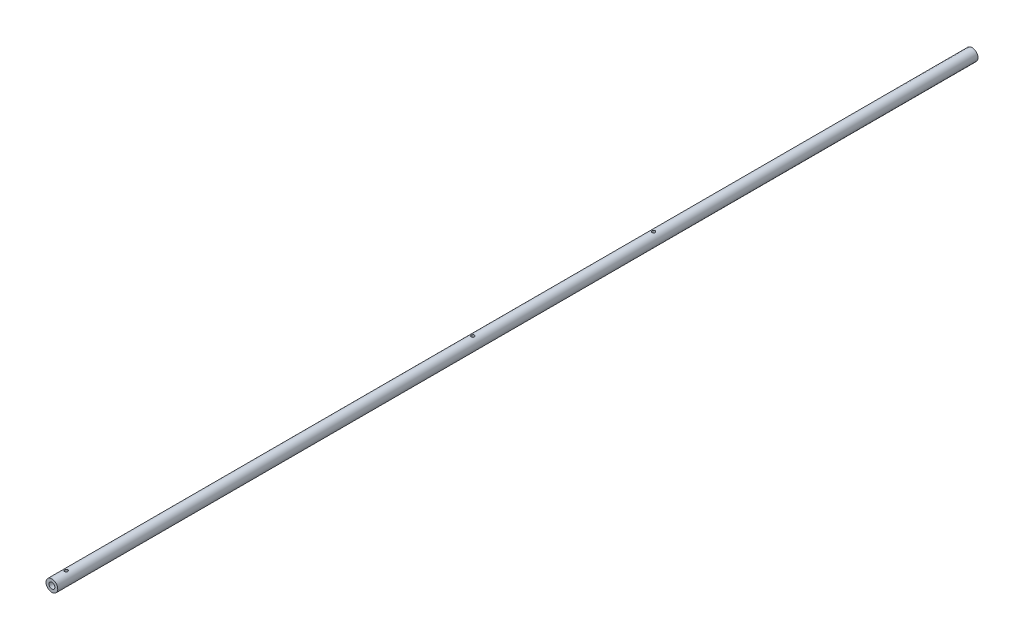
SolidWorks part; units mm, degrees
ref_plane "Front Plane" through (0, 0, 0) normal (0, 0, 1) x (1, 0, 0)
ref_plane "Top Plane" through (0, 0, 0) normal (0, 1, 0) x (1, 0, 0)
ref_plane "Right Plane" through (0, 0, 0) normal (1, 0, 0) x (0, 0, -1)
sketch "Sketch1" plane through (0, 0, 0) normal (0, 0, 1) x (1, 0, 0)
  circle A0 centre (0, 0) radius 3.9306
  circle A1 centre (0, 0) radius 7.8613
  dimension "D1" = 15.7226
  dimension "D2" = 7.8613
extrude "Rod" add sketch "Sketch1" along normal blind 1228.725 contours A0
sketch "Sketch3" plane through (0, 0, 0) normal (0, 1, 0) x (1, 0, 0)
  line L0 (0, -425.45) -> (0, -962.025) construction
  line L1 (-7.8613, -1228.725) -> (7.8613, -1228.725) construction
  circle A0 centre (0, -425.45) radius 2.1082
  circle A4 centre (0, -666.75) radius 2.1082
  circle A5 centre (0, -1209.675) radius 2.1082
  dimension "D1" = 4.2164
  dimension "D6" = 4.2164
  dimension "D2" = 425.45
  dimension "D4" = 241.3
  dimension "D5" = 536.575
  dimension "D7" = 19.05
  dimension "D3" = 2
extrude "Holes" cut sketch "Sketch3" against normal through all both and the other way through all
ref_plane "Handle Location" through (0, 0, 962.025) normal (0, 0, 1) x (1, 0, 0)
equation "\"L\"= 48.375"
equation "\"D1@Rod\" = \"L\""
equation "\"N\"= 2"
equation "\"D3@Sketch3\"=\"N\""
equation "\"S\"= 9.5"
equation "\"D4@Sketch3\"=\"S\""
equation "\"O\"= 16.75"
equation "\"D2@Sketch3\"=\"O\""
equation "\"H\"= 21.125"
equation "\"D5@Sketch3\"=\"H\""
